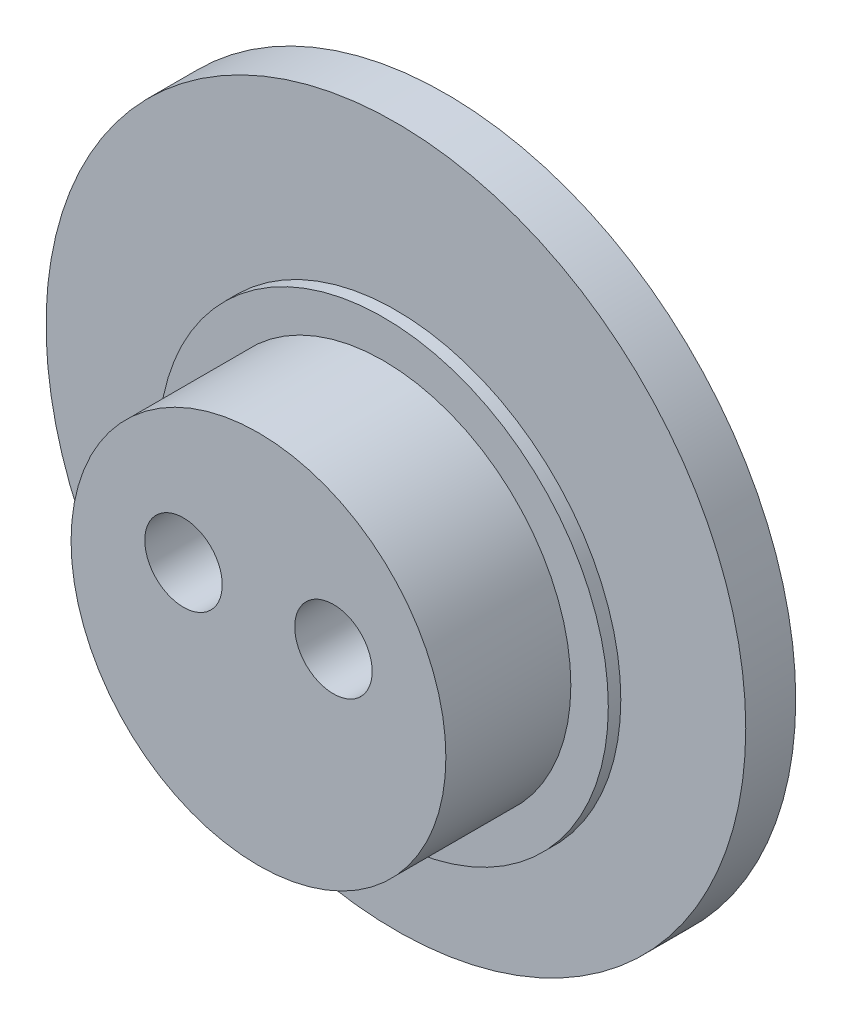
SolidWorks part; units mm, degrees
ref_plane "Front Plane" through (0, 0, 0) normal (0, 0, 1) x (1, 0, 0)
ref_plane "Top Plane" through (0, 0, 0) normal (0, 1, 0) x (1, 0, 0)
ref_plane "Right Plane" through (0, 0, 0) normal (1, 0, 0) x (0, 0, -1)
sketch "Sketch1" plane through (0, 0, 0) normal (0, 0, 1) x (1, 0, 0)
  circle A0 centre (0, 0) radius 14
  dimension "D1" = 28
extrude "Boss-Extrude1" add sketch "Sketch1" along normal blind 2
sketch "Sketch2" plane through (0, 0, 2) normal (0, 0, 1) x (1, 0, 0)
  line L0 (0, 14.3027) -> (0, -14.8918) construction
  circle A0 centre (0, -1.5) radius 9
  dimension "D1" = 18
  dimension "D2" = 1.5
extrude "Boss-Extrude2" add sketch "Sketch2" along normal blind 0.5
sketch "Sketch4" plane through (0, 0, 2.5) normal (0, 0, 1) x (1, 0, 0)
  line L0 (0, 14.4009) -> (0, -15.2846) construction
  circle A0 centre (0, -1.5) radius 7.5
  dimension "D1" = 15
  dimension "D2" = 1.5
extrude "Boss-Extrude3" add sketch "Sketch4" along normal blind 5
sketch "Sketch6" plane through (0, 0, 0) normal (0, 0, -1) x (-1, 0, 0)
  line L0 (0, 14.5318) -> (0, -15.3828) construction
  circle A0 centre (0, 1.5) radius 9
  dimension "D1" = 18
  dimension "D2" = 1.5
extrude "Boss-Extrude4" add sketch "Sketch6" along normal blind 0.5
sketch "Sketch5" plane through (0, 0, 7.5) normal (0, 0, 1) x (1, 0, 0)
  line L0 (-16.3319, 0) -> (18.0666, 0) construction
  line L1 (0, 14.4664) -> (0, -15.5137) construction
  circle A0 centre (3, 0) radius 1.55
  circle A1 centre (-3, 0) radius 1.55
  dimension "D2" = 3.1
  dimension "D1" = 0
  dimension "D3" = 3
extrude "Cut-Extrude1" cut sketch "Sketch5" against normal through all
